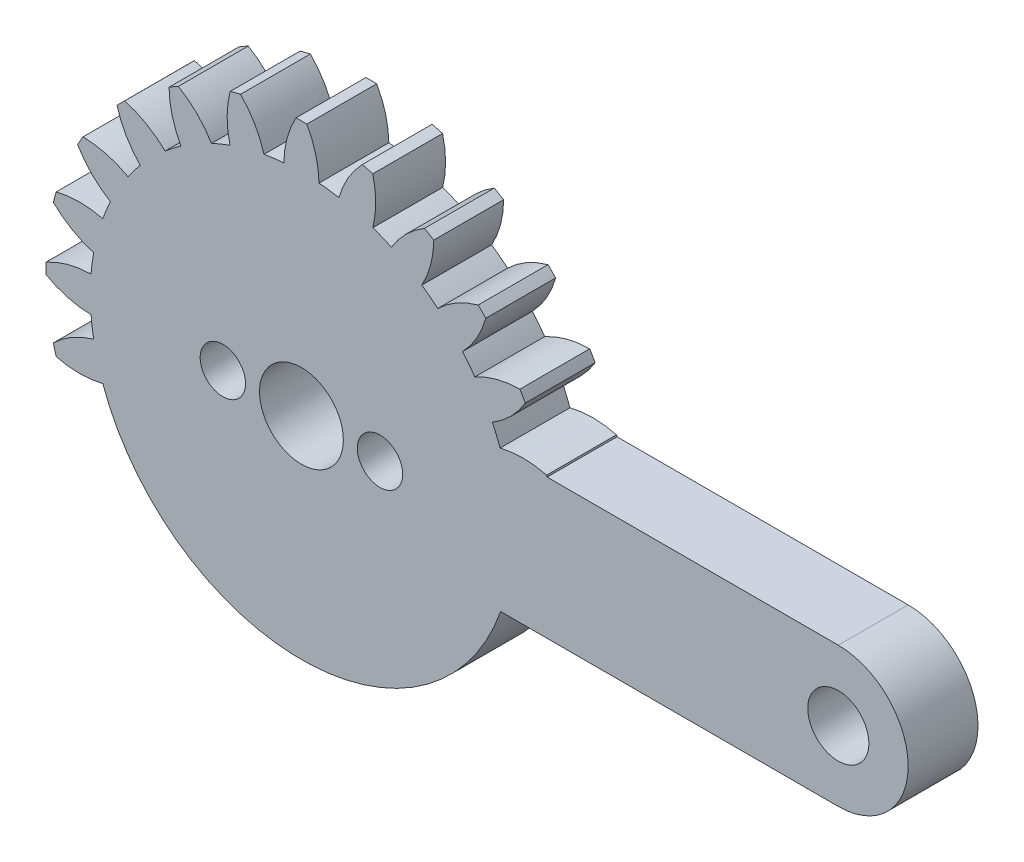
SolidWorks part; units mm, degrees
ref_plane "Front Plane" through (0, 0, 0) normal (0, 0, 1) x (1, 0, 0)
ref_plane "Top Plane" through (0, 0, 0) normal (0, 1, 0) x (1, 0, 0)
ref_plane "Right Plane" through (0, 0, 0) normal (1, 0, 0) x (0, 0, -1)
sketch "Sketch1" plane through (0, 0, 0) normal (0, 0, 1) x (1, 0, 0)
  line L0 (0, 0) -> (0, 14.63) construction
  line L1 (0, 0) -> (39.758, 0) construction
  line L2 (11.4091, 4) -> (30.75, 4)
  line L3 (30.75, -4) -> (11.4091, -4)
  circle A0 centre (0, 0) radius 12.09
  circle A1 centre (0, 0) radius 1.75
  circle A2 centre (0, 0) radius 14.63
  arc A3 (-0.31, 14.6267) -> (-1.0062, 12.0481) centre (4.3933, 11.9736) ccw
  arc A4 (0.31, 14.6267) -> (1.0062, 12.0481) centre (-4.3933, 11.9736) cw
  arc A5 (4.0851, 14.0481) -> (4.0902, 11.3771) centre (-1.1446, 12.7027) cw
  arc A6 (3.4862, 14.2086) -> (2.1464, 11.898) centre (7.3426, 10.4285) ccw
  arc A7 (7.5818, 12.5121) -> (6.8954, 9.9308) centre (2.1821, 12.5661) cw
  arc A8 (7.0449, 12.8221) -> (5.1526, 10.937) centre (9.7915, 8.1728) ccw
  arc A9 (10.5619, 10.1234) -> (9.2308, 7.8078) centre (5.3601, 11.5731) cw
  arc A10 (10.1234, 10.5619) -> (7.8078, 9.2308) centre (11.5731, 5.3601) ccw
  arc A11 (12.8221, 7.0449) -> (10.937, 5.1526) centre (8.1728, 9.7915) cw
  arc A12 (12.5121, 7.5818) -> (9.9308, 6.8954) centre (12.5661, 2.1821) ccw
  arc A13 (14.2086, 3.4862) -> (11.898, 2.1464) centre (10.4285, 7.3426) cw
  arc A14 (14.0481, 4.0851) -> (11.3771, 4.0902) centre (12.7027, -1.1446) ccw
  arc A15 (14.6267, -0.31) -> (12.0481, -1.0062) centre (11.9736, 4.3933) cw
  arc A16 (14.6267, 0.31) -> (12.0481, 1.0062) centre (11.9736, -4.3933) ccw
  arc A17 (14.0481, -4.0851) -> (11.3771, -4.0902) centre (12.7027, 1.1446) cw
  arc A18 (14.2086, -3.4862) -> (11.898, -2.1464) centre (10.4285, -7.3426) ccw
  arc A19 (12.5121, -7.5818) -> (9.9308, -6.8954) centre (12.5661, -2.1821) cw
  arc A20 (12.8221, -7.0449) -> (10.937, -5.1526) centre (8.1728, -9.7915) ccw
  arc A21 (10.1234, -10.5619) -> (7.8078, -9.2308) centre (11.5731, -5.3601) cw
  arc A22 (10.5619, -10.1234) -> (9.2308, -7.8078) centre (5.3601, -11.5731) ccw
  arc A23 (7.0449, -12.8221) -> (5.1526, -10.937) centre (9.7915, -8.1728) cw
  arc A24 (7.5818, -12.5121) -> (6.8954, -9.9308) centre (2.1821, -12.5661) ccw
  arc A25 (3.4862, -14.2086) -> (2.1464, -11.898) centre (7.3426, -10.4285) cw
  arc A26 (4.0851, -14.0481) -> (4.0902, -11.3771) centre (-1.1446, -12.7027) ccw
  arc A27 (-0.31, -14.6267) -> (-1.0062, -12.0481) centre (4.3933, -11.9736) cw
  arc A28 (0.31, -14.6267) -> (1.0062, -12.0481) centre (-4.3933, -11.9736) ccw
  arc A29 (-4.0851, -14.0481) -> (-4.0902, -11.3771) centre (1.1446, -12.7027) cw
  arc A30 (-3.4862, -14.2086) -> (-2.1464, -11.898) centre (-7.3426, -10.4285) ccw
  arc A31 (-7.5818, -12.5121) -> (-6.8954, -9.9308) centre (-2.1821, -12.5661) cw
  arc A32 (-7.0449, -12.8221) -> (-5.1526, -10.937) centre (-9.7915, -8.1728) ccw
  arc A33 (-10.5619, -10.1234) -> (-9.2308, -7.8078) centre (-5.3601, -11.5731) cw
  arc A34 (-10.1234, -10.5619) -> (-7.8078, -9.2308) centre (-11.5731, -5.3601) ccw
  arc A35 (-12.8221, -7.0449) -> (-10.937, -5.1526) centre (-8.1728, -9.7915) cw
  arc A36 (-12.5121, -7.5818) -> (-9.9308, -6.8954) centre (-12.5661, -2.1821) ccw
  arc A37 (-14.2086, -3.4862) -> (-11.898, -2.1464) centre (-10.4285, -7.3426) cw
  arc A38 (-14.0481, -4.0851) -> (-11.3771, -4.0902) centre (-12.7027, 1.1446) ccw
  arc A39 (-14.6267, 0.31) -> (-12.0481, 1.0062) centre (-11.9736, -4.3933) cw
  arc A40 (-14.6267, -0.31) -> (-12.0481, -1.0062) centre (-11.9736, 4.3933) ccw
  arc A41 (-14.0481, 4.0851) -> (-11.3771, 4.0902) centre (-12.7027, -1.1446) cw
  arc A42 (-14.2086, 3.4862) -> (-11.898, 2.1464) centre (-10.4285, 7.3426) ccw
  arc A43 (-12.5121, 7.5818) -> (-9.9308, 6.8954) centre (-12.5661, 2.1821) cw
  arc A44 (-12.8221, 7.0449) -> (-10.937, 5.1526) centre (-8.1728, 9.7915) ccw
  arc A45 (-10.1234, 10.5619) -> (-7.8078, 9.2308) centre (-11.5731, 5.3601) cw
  arc A46 (-10.5619, 10.1234) -> (-9.2308, 7.8078) centre (-5.3601, 11.5731) ccw
  arc A47 (-7.0449, 12.8221) -> (-5.1526, 10.937) centre (-9.7915, 8.1728) cw
  arc A48 (-7.5818, 12.5121) -> (-6.8954, 9.9308) centre (-2.1821, 12.5661) ccw
  arc A49 (-3.4862, 14.2086) -> (-2.1464, 11.898) centre (-7.3426, 10.4285) cw
  arc A50 (-4.0851, 14.0481) -> (-4.0902, 11.3771) centre (1.1446, 12.7027) ccw
  arc A51 (30.75, 4) -> (30.75, -4) centre (30.75, 0) cw
  circle A52 centre (30.75, 0) radius 1.75
  point P153 (0, 0)
  point P156 (0, 0)
  point P159 (-48.6434, 17.4636)
  dimension "D1" = 3.5
  dimension "D2" = 24.18
  dimension "D3" = 29.26
  dimension "D6" = 5.4
  dimension "D8" = 30.75
  dimension "D9" = 4
  dimension "D10" = 3.5
  dimension "D4" = 0.62
  dimension "D11" = 1.15
  dimension "D7" = 24
extrude "Boss-Extrude1" add sketch "Sketch1" along normal blind 4 contours A51 L2 A2 L3 A52 | A2 A18 A0 L3 | A18 A2 A15 A0 | A2 A16 A0 A15 | A16 A2 A13 A0 | A13 A2 L2 A0 | A2 A14 A0 L2 | A2 A12 A0 A11 | A2 A10 A0 A9 | A2 A8 A0 A7 | A2 A6 A0 A5 | A4 A2 A3 A0 | A2 A50 A0 A49 | A2 A48 A0 A47 | A2 A46 A0 A45 | A2 A44 A0 A43 | A2 A42 A0 A41 | A2 A40 A0 A39 | A2 A38 A0 A37 | A0 L3
sketch "Sketch2" plane through (0, 0, 4) normal (0, 0, 1) x (1, 0, 0)
  line L0 (-4.5, 0) -> (4.5, 0) construction
  circle A0 centre (4.5, 0) radius 1.3
  circle A1 centre (-4.5, 0) radius 1.3
  circle A2 centre (0, 0) radius 2.4
  point P4 (0, 0)
  dimension "D3" = 2.6
  dimension "D1" = 4.8
  dimension "D2" = 9
extrude "Cut-Extrude1" cut sketch "Sketch2" against normal through all
